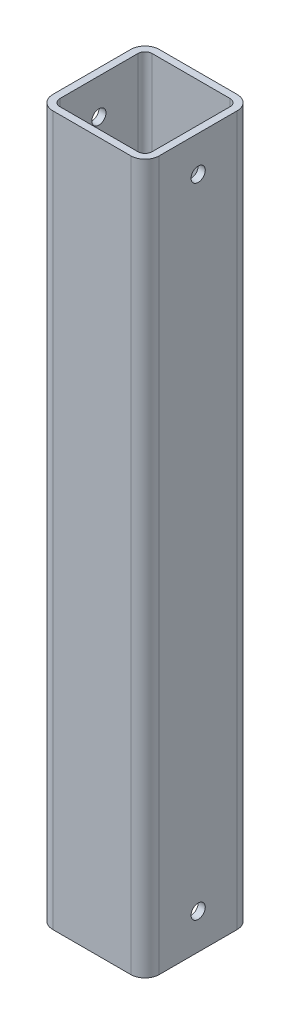
SolidWorks part; units mm, degrees
ref_plane "前视基准面" through (0, 0, 0) normal (0, 0, 1) x (1, 0, 0)
ref_plane "上视基准面" through (0, 0, 0) normal (0, 1, 0) x (1, 0, 0)
ref_plane "右视基准面" through (0, 0, 0) normal (1, 0, 0) x (0, 0, -1)
sketch "草图1" plane through (0, 0, 0) normal (0, 1, 0) x (1, 0, 0)
  line L0 (-11, -13) -> (11, -13)
  line L1 (-11, -15) -> (11, -15)
  line L2 (-15, -11) -> (-15, 11)
  line L3 (-11, 15) -> (11, 15)
  line L4 (15, -11) -> (15, 11)
  line L5 (13, -11) -> (13, 11)
  line L6 (-11, 13) -> (11, 13)
  line L7 (-13, -11) -> (-13, 11)
  arc A0 (-11, -15) -> (-15, -11) centre (-11, -11) cw
  arc A1 (11, -15) -> (15, -11) centre (11, -11) ccw
  arc A2 (11, 15) -> (15, 11) centre (11, 11) cw
  arc A3 (-15, 11) -> (-11, 15) centre (-11, 11) cw
  arc A4 (11, -13) -> (13, -11) centre (11, -11) ccw
  arc A5 (11, 13) -> (13, 11) centre (11, 11) cw
  arc A6 (-13, 11) -> (-11, 13) centre (-11, 11) cw
  arc A7 (-11, -13) -> (-13, -11) centre (-11, -11) cw
extrude "凸台-拉伸1" add sketch "草图1" along normal mid plane 200
sketch "草图2" plane through (0, 0, 0) normal (1, 0, 0) x (0, 0, -1)
  line L0 (-15, 0) -> (15, 0) construction
  line L1 (-15, 100) -> (-15, -100) construction
  line L2 (15, 100) -> (15, -100) construction
  circle A0 centre (0, 90) radius 2
  circle A1 centre (0, -90) radius 2
  point P10 (0, 0)
  dimension "D1" = 4
  dimension "D2" = 90
extrude "切除-拉伸1" cut sketch "草图2" against normal through all both and the other way through all
